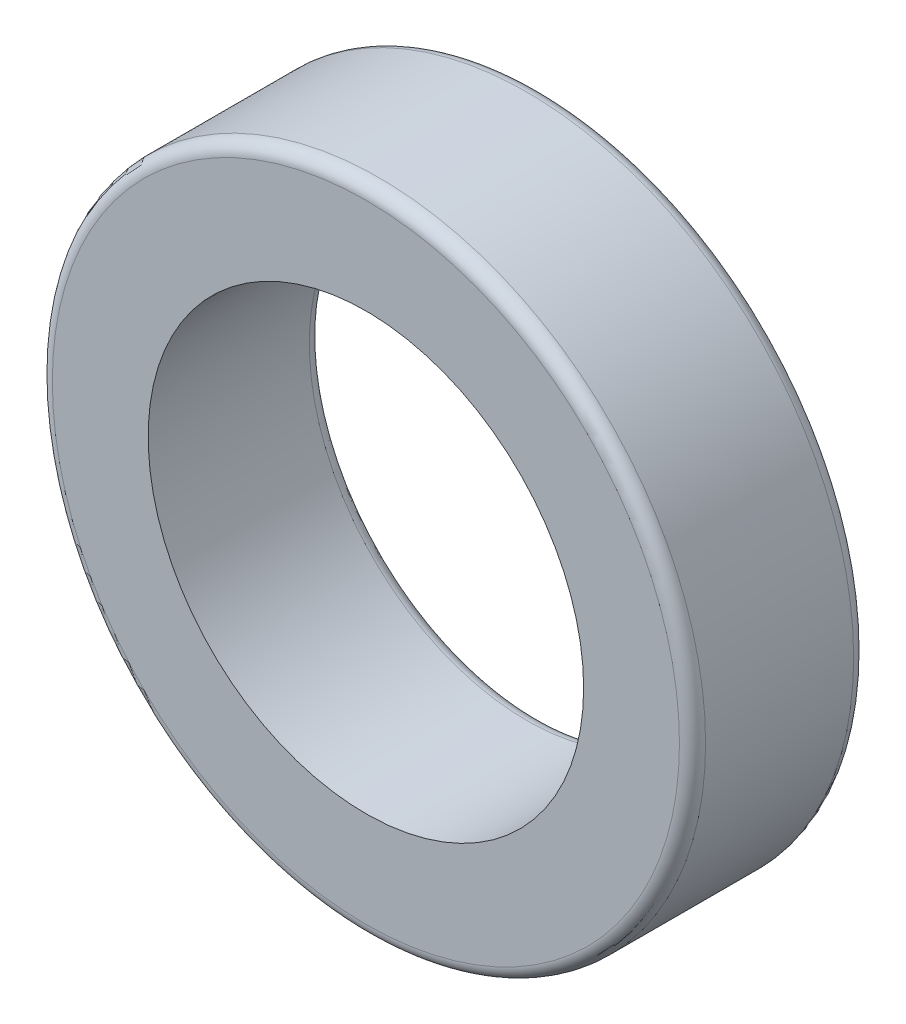
SolidWorks part; units mm, degrees
material "Plain Carbon Steel"
ref_plane "Front Plane" through (0, 0, 0) normal (0, 0, 1) x (1, 0, 0)
ref_plane "Top Plane" through (0, 0, 0) normal (0, 1, 0) x (1, 0, 0)
ref_plane "Right Plane" through (0, 0, 0) normal (1, 0, 0) x (0, 0, -1)
sketch "Sketch1" plane through (0, 0, 0) normal (0, 0, 1) x (1, 0, 0)
  circle A0 centre (0, 0) radius 7.5
  circle A1 centre (0, 0) radius 5
  dimension "D1" = 10
  dimension "D2" = 15
extrude "Boss-Extrude1" add sketch "Sketch1" along normal mid plane 4
fillet "Fillet2" radius 0.3 3 edges at (7.5, 0, 2) (7.5, 0, -2) (5, 0, -2)
